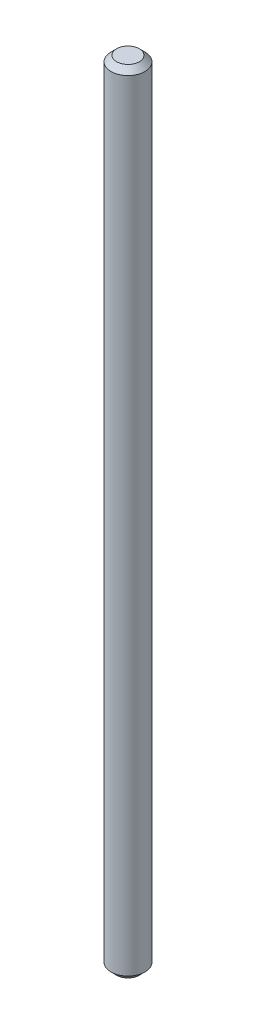
SolidWorks part; units mm, degrees
ref_plane "Front Plane" through (0, 0, 0) normal (0, 0, 1) x (1, 0, 0)
ref_plane "Top Plane" through (0, 0, 0) normal (0, 1, 0) x (1, 0, 0)
ref_plane "Right Plane" through (0, 0, 0) normal (1, 0, 0) x (0, 0, -1)
sketch "Sketch1" plane through (0, 0, 0) normal (0, 1, 0) x (1, 0, 0)
  circle A0 centre (0, 0) radius 3
  dimension "D1" = 6
extrude "Boss-Extrude1" add sketch "Sketch1" along normal blind 140
chamfer "Chamfer1" distance 1 angle 45 2 edges at (0, 0, 3) (0, 140, 3)
